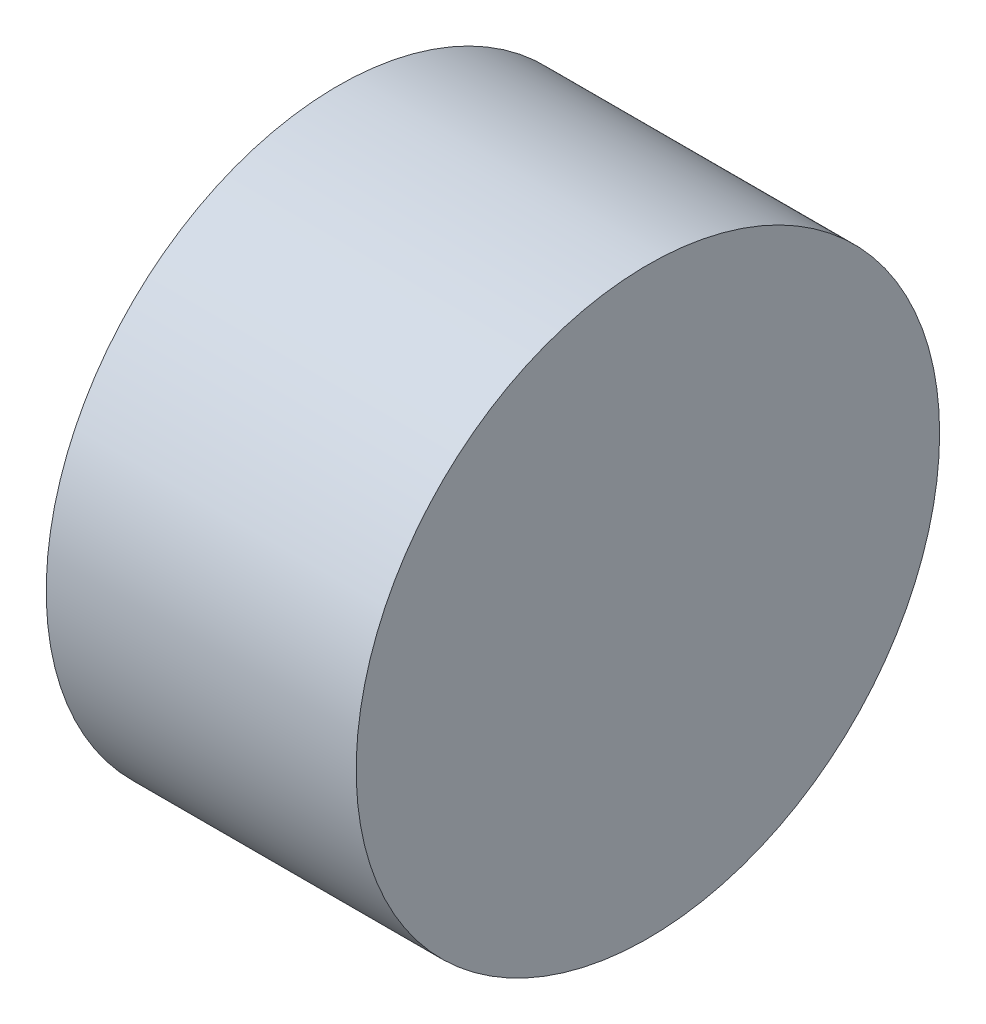
SolidWorks part; units mm, degrees
ref_plane "Plano frontal" through (0, 0, 0) normal (0, 0, 1) x (1, 0, 0)
ref_plane "Plano superior" through (0, 0, 0) normal (0, 1, 0) x (1, 0, 0)
ref_plane "Plano direito" through (0, 0, 0) normal (1, 0, 0) x (0, 0, -1)
sketch "Esboço1" plane through (0, 0, 0) normal (0, 0, 1) x (1, 0, 0)
  line L0 (0, 0) -> (-120.7611, 0) construction
  line L1 (0, 0) -> (0, 16)
  line L2 (0, 16) -> (-17, 16)
  line L3 (-17, 16) -> (-17, 11)
  line L4 (-17, 11) -> (-3, 11)
  line L5 (-3, 11) -> (-3, 5)
  line L6 (-3, 5) -> (-12, 5)
  line L7 (-12, 5) -> (-12, 2)
  line L8 (-12, 2) -> (-3, 2)
  line L9 (-3, 2) -> (-3, 0)
  line L10 (-3, 0) -> (0, 0)
  dimension "D1" = 2
  dimension "D2" = 3
  dimension "D3" = 3
  dimension "D4" = 16
  dimension "D5" = 5
  dimension "D6" = 17
  dimension "D7" = 9
revolve "Revolução1" add sketch "Esboço1" angle 360 about L0
